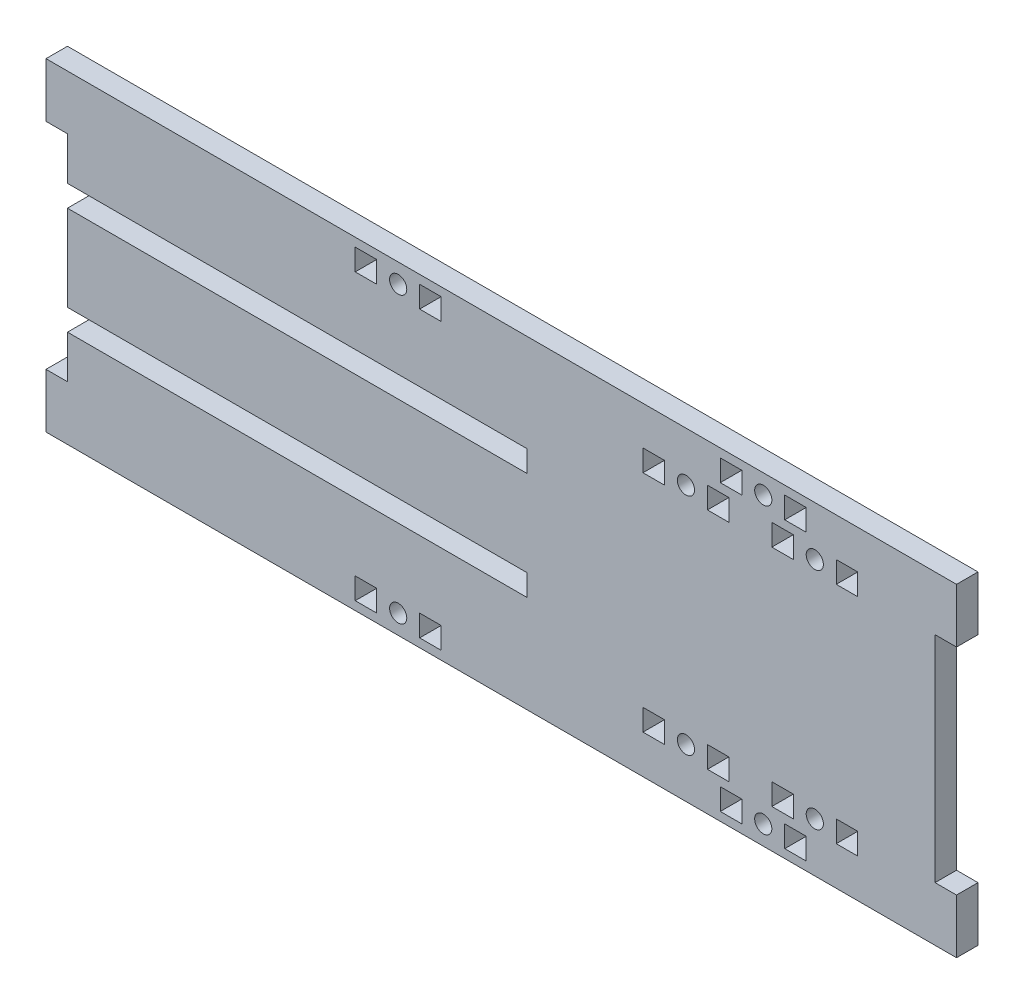
SolidWorks part; units mm, degrees
ref_plane "Plan de face" through (0, 0, 0) normal (0, 0, 1) x (1, 0, 0)
ref_plane "Plan de dessus" through (0, 0, 0) normal (0, 1, 0) x (1, 0, 0)
ref_plane "Plan de droite" through (0, 0, 0) normal (1, 0, 0) x (0, 0, -1)
sketch "Esquisse1" plane through (0, 0, 0) normal (0, 0, 1) x (1, 0, 0)
  line L0 (0, 0) -> (162, 0) construction
  line L1 (0, 37.65) -> (162, 37.65)
  line L2 (162, 37.65) -> (162, -37.65) construction
  line L3 (0, 37.65) -> (0, -37.65) construction
  line L4 (0, -37.65) -> (162, -37.65)
  line L5 (0, 37.65) -> (-50, 37.65)
  line L6 (162, 37.65) -> (162, 25)
  line L8 (-45, 10) -> (0, 10)
  line L9 (0, 10) -> (62, 10)
  line L10 (62, 10) -> (-45, 10)
  line L13 (-45, -10) -> (62, -10)
  line L14 (62, -10) -> (62, -15)
  line L15 (62, -15) -> (-50, -15) construction
  line L16 (-50, -15) -> (-50, -37.65) construction
  line L17 (162, 25) -> (157, 25)
  line L18 (-50, -37.65) -> (0, -37.65)
  line L19 (-45, 10) -> (-45, -10)
  line L20 (62, 10) -> (62, 15)
  line L21 (62, 15) -> (-50, 15) construction
  line L22 (-50, 15) -> (-50, 37.65) construction
  line L23 (157, 25) -> (157, -25)
  line L24 (157, -25) -> (162, -25)
  line L25 (162, -25) -> (162, -37.65)
  line L26 (-50, 37.65) -> (-50, 25)
  line L27 (-50, 25) -> (-45, 25)
  line L28 (-45, 25) -> (-45, 15)
  line L29 (-45, 15) -> (62, 15)
  line L30 (-45, -15) -> (62, -15)
  line L31 (-45, -25) -> (-45, -15)
  line L32 (-50, -25) -> (-45, -25)
  line L33 (-50, -37.65) -> (-50, -25)
  point P28 (99, -22.6638)
  point P29 (0, 0)
  line B0 (112, 33.15) -> (122, 33.15) construction
  line B1 (112, 35.65) -> (107, 35.65)
  line B2 (112, 35.65) -> (112, 30.65)
  line B3 (112, 30.65) -> (107, 30.65)
  line B4 (107, 35.65) -> (107, 30.65)
  line B5 (122, 35.65) -> (127, 35.65)
  line B6 (122, 35.65) -> (122, 30.65)
  line B7 (122, 30.65) -> (127, 30.65)
  line B8 (127, 35.65) -> (127, 30.65)
  line B9 (117, 33.15) -> (117, 40.1224) construction
  circle B10 centre (117, 33.15) radius 2
  line B11 (112, -33.15) -> (122, -33.15) construction
  line B12 (112, -35.65) -> (107, -35.65)
  line B13 (112, -35.65) -> (112, -30.65)
  line B14 (112, -30.65) -> (107, -30.65)
  line B15 (107, -35.65) -> (107, -30.65)
  line B16 (122, -35.65) -> (127, -35.65)
  line B17 (122, -35.65) -> (122, -30.65)
  line B18 (122, -30.65) -> (127, -30.65)
  line B19 (127, -35.65) -> (127, -30.65)
  line B20 (117, -33.15) -> (117, -40.1224) construction
  circle B21 centre (117, -33.15) radius 2
  line B22 (27, 33.15) -> (37, 33.15) construction
  line B23 (27, 35.65) -> (22, 35.65)
  line B24 (27, 35.65) -> (27, 30.65)
  line B25 (27, 30.65) -> (22, 30.65)
  line B26 (22, 35.65) -> (22, 30.65)
  line B27 (37, 35.65) -> (42, 35.65)
  line B28 (37, 35.65) -> (37, 30.65)
  line B29 (37, 30.65) -> (42, 30.65)
  line B30 (42, 35.65) -> (42, 30.65)
  line B31 (32, 33.15) -> (32, 40.1224) construction
  circle B32 centre (32, 33.15) radius 2
  line B33 (27, -33.15) -> (37, -33.15) construction
  line B34 (27, -35.65) -> (22, -35.65)
  line B35 (27, -35.65) -> (27, -30.65)
  line B36 (27, -30.65) -> (22, -30.65)
  line B37 (22, -35.65) -> (22, -30.65)
  line B38 (37, -35.65) -> (42, -35.65)
  line B39 (37, -35.65) -> (37, -30.65)
  line B40 (37, -30.65) -> (42, -30.65)
  line B41 (42, -35.65) -> (42, -30.65)
  line B42 (32, -33.15) -> (32, -40.1224) construction
  circle B43 centre (32, -33.15) radius 2
  line B44 (94, -26.15) -> (104, -26.15) construction
  line B45 (94, -23.65) -> (89, -23.65)
  line B46 (94, -23.65) -> (94, -28.65)
  line B47 (94, -28.65) -> (89, -28.65)
  line B48 (89, -23.65) -> (89, -28.65)
  line B49 (104, -23.65) -> (109, -23.65)
  line B50 (104, -23.65) -> (104, -28.65)
  line B51 (104, -28.65) -> (109, -28.65)
  line B52 (109, -23.65) -> (109, -28.65)
  line B53 (99, -26.15) -> (99, -19.1776) construction
  circle B54 centre (99, -26.15) radius 2
  line B55 (124, -26.15) -> (134, -26.15) construction
  line B56 (124, -23.65) -> (119, -23.65)
  line B57 (124, -23.65) -> (124, -28.65)
  line B58 (124, -28.65) -> (119, -28.65)
  line B59 (119, -23.65) -> (119, -28.65)
  line B60 (134, -23.65) -> (139, -23.65)
  line B61 (134, -23.65) -> (134, -28.65)
  line B62 (134, -28.65) -> (139, -28.65)
  line B63 (139, -23.65) -> (139, -28.65)
  line B64 (129, -26.15) -> (129, -19.1776) construction
  circle B65 centre (129, -26.15) radius 2
  line B66 (124, 26.15) -> (134, 26.15) construction
  line B67 (124, 23.65) -> (119, 23.65)
  line B68 (124, 23.65) -> (124, 28.65)
  line B69 (124, 28.65) -> (119, 28.65)
  line B70 (119, 23.65) -> (119, 28.65)
  line B71 (134, 23.65) -> (139, 23.65)
  line B72 (134, 23.65) -> (134, 28.65)
  line B73 (134, 28.65) -> (139, 28.65)
  line B74 (139, 23.65) -> (139, 28.65)
  line B75 (129, 26.15) -> (129, 19.1776) construction
  circle B76 centre (129, 26.15) radius 2
  line B77 (94, 26.15) -> (104, 26.15) construction
  line B78 (94, 23.65) -> (89, 23.65)
  line B79 (94, 23.65) -> (94, 28.65)
  line B80 (94, 28.65) -> (89, 28.65)
  line B81 (89, 23.65) -> (89, 28.65)
  line B82 (104, 23.65) -> (109, 23.65)
  line B83 (104, 23.65) -> (104, 28.65)
  line B84 (104, 28.65) -> (109, 28.65)
  line B85 (109, 23.65) -> (109, 28.65)
  line B86 (99, 26.15) -> (99, 19.1776) construction
  circle B87 centre (99, 26.15) radius 2
  dimension "D1" = 45
  dimension "D2" = 212
  dimension "D3" = 2
  dimension "D4" = 112
  dimension "D5" = 33.15
  dimension "D6" = 5
  dimension "D7" = 50
  dimension "D8" = 20
  dimension "D9" = 20
  dimension "D10" = 85
  dimension "D11" = 100
  dimension "D12" = 5
  dimension "D13" = 30
  dimension "D14" = 5
  dimension "D15" = 5
  dimension "D16" = 10
  dimension "D17" = 30
  dimension "D18" = 2
  dimension "D19" = 58
  dimension "D20" = 30
sketch_block_instance "Trou M4 plots 5mm-1"
sketch_block "Trou M4 plots 5mm" parameters "D2"=4, "D1"=5, "D3"=5, "D4"=10
sketch_block_instance "Trou M4 plots 5mm-5"
sketch_block_instance "Trou M4 plots 5mm-6"
sketch_block_instance "Trou M4 plots 5mm-7"
sketch_block_instance "Trou M4 plots 5mm-9"
sketch_block_instance "Trou M4 plots 5mm-10"
sketch_block_instance "Trou M4 plots 5mm-12"
sketch_block_instance "Trou M4 plots 5mm-13"
extrude "Boss.-Extru.1" add sketch "Esquisse1" along normal blind 5 contours L22 L21 L20 L9 L8 L19 L13 L14 L15 L16 L18 L4 L2 L1 L5 B34 B37 B36 B35 B27 B30 B29 B28 B21 B19 B16 B17 B18 B10 B4 B1 B2 B3 B5 B8 B7 B6 B12 B15 B14 B13 B26
